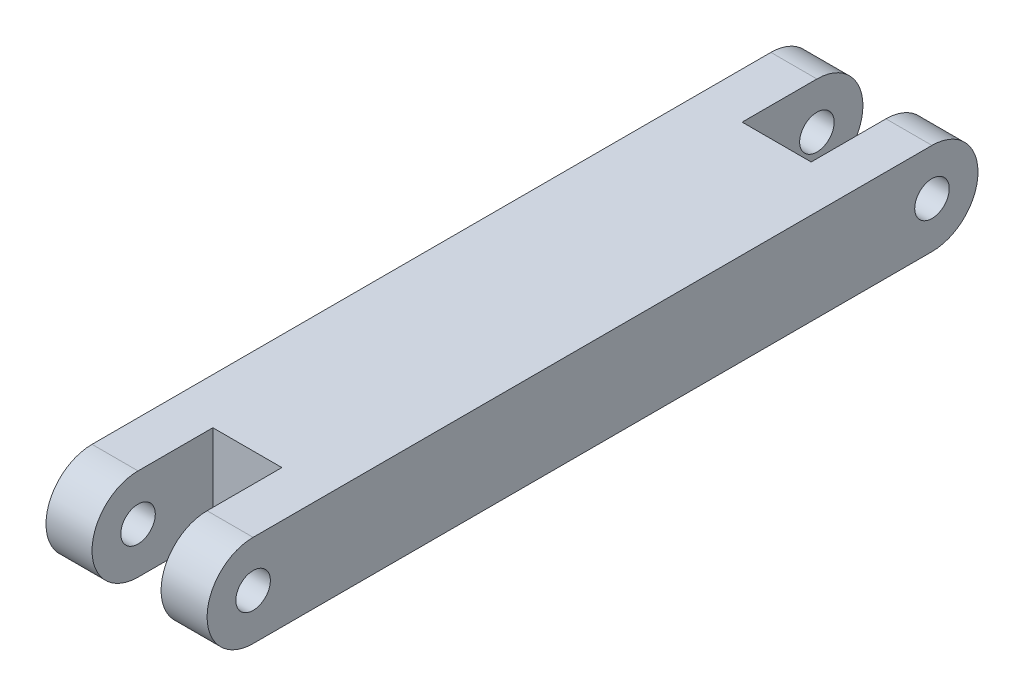
SolidWorks part; units mm, degrees
material "3.0205 (EN-AW 1200)"
ref_plane "Alzado" through (0, 0, 0) normal (0, 0, 1) x (1, 0, 0)
ref_plane "Planta" through (0, 0, 0) normal (0, 1, 0) x (1, 0, 0)
ref_plane "Vista lateral" through (0, 0, 0) normal (1, 0, 0) x (0, 0, -1)
sketch "Croquis1" plane through (0, 0, 0) normal (1, 0, 0) x (0, 0, -1)
  line L0 (-29.5, 0) -> (29.5, 0) construction
  line L1 (-29.5, 4) -> (29.5, 4)
  line L2 (-29.5, -4) -> (29.5, -4)
  arc A0 (-29.5, 4) -> (-29.5, -4) centre (-29.5, 0) ccw
  arc A1 (29.5, -4) -> (29.5, 4) centre (29.5, 0) ccw
  circle A2 centre (-29.5, 0) radius 1.5
  circle A3 centre (29.5, 0) radius 1.5
  point P2 (0, 0)
  dimension "D2" = 4
  dimension "D3" = 3
  dimension "D1" = 59
extrude "Saliente-Extruir1" add sketch "Croquis1" along normal blind 4
sketch "Croquis2" plane through (0, 0, 0) normal (0, 0, 1) x (1, 0, 0)
  line L1 (4, 4) -> (10, 4)
  line L2 (4, 4) -> (4, -4)
  line L3 (4, -4) -> (10, -4)
  line L4 (10, 4) -> (10, -4)
  dimension "D1" = 8
  dimension "D2" = 6
extrude "Saliente-Extruir2" add sketch "Croquis2" along normal mid plane 46
sketch "Croquis3" plane through (10, 0, 0) normal (1, 0, 0) x (0, 0, -1)
  line L0 (-29.5, 0) -> (29.5, 0) construction
  line L1 (-29.5, 4) -> (29.5, 4)
  line L2 (-29.5, -4) -> (29.5, -4)
  arc A0 (-29.5, 4) -> (-29.5, -4) centre (-29.5, 0) ccw
  arc A1 (29.5, -4) -> (29.5, 4) centre (29.5, 0) ccw
  circle A2 centre (-29.5, 0) radius 1.5
  circle A3 centre (29.5, 0) radius 1.5
  point P2 (0, 0)
  dimension "D1" = 4
  dimension "D2" = 3
  dimension "D3" = 3
extrude "Saliente-Extruir3" add sketch "Croquis3" along normal blind 4
sketch "Croquis4" [suppressed] plane through (0, -4, 0) normal (0, -1, 0) x (1, 0, 0)
  line L0 (10, -23) -> (11.6, -23)
  line L1 (11.6, -23) -> (11.6, -37.2112)
  line L2 (11.6, -37.2112) -> (10, -37.2112)
  line L3 (10, -37.2112) -> (10, -23)
  dimension "D1" = 1.6
extrude "Cortar-Extruir1" [suppressed] cut sketch "Croquis4" against normal blind 10
